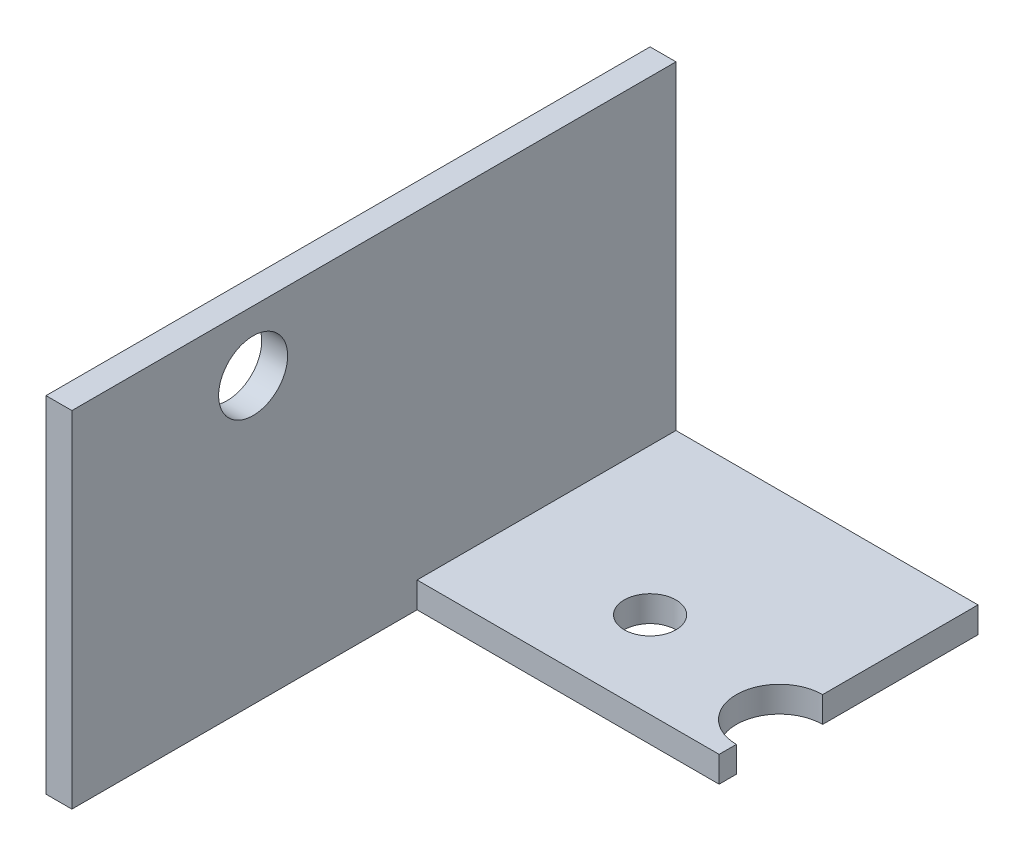
SolidWorks part; units mm, degrees
ref_plane "Plan de face" through (0, 0, 0) normal (0, 0, 1) x (1, 0, 0)
ref_plane "Plan de dessus" through (0, 0, 0) normal (0, 1, 0) x (1, 0, 0)
ref_plane "Plan de droite" through (0, 0, 0) normal (1, 0, 0) x (0, 0, -1)
sketch "Esquisse1" plane through (0, 0, 0) normal (0, 0, 1) x (1, 0, 0)
  line L0 (-13.4546, 9.7732) -> (-13.4546, -10.2268)
  line L1 (-13.4546, -10.2268) -> (5.5454, -10.2268)
  line L2 (5.5454, -10.2268) -> (5.5454, -8.7268)
  line L3 (5.5454, -8.7268) -> (-11.9546, -8.7268)
  line L4 (-11.9546, -8.7268) -> (-11.9546, 9.7732)
  line L5 (-11.9546, 9.7732) -> (-13.4546, 9.7732)
  dimension "D1" = 1.5
  dimension "D2" = 1.5
  dimension "D3" = 19
  dimension "D4" = 20
extrude "Extrusion1" add sketch "Esquisse1" along normal blind 35
sketch "Esquisse2" plane through (-11.9546, 0, 0) normal (1, 0, 0) x (0, 0, -1)
  line L0 (-35, -8.7268) -> (-35, 9.7732) construction
  line L1 (-35, 9.7732) -> (0, 9.7732) construction
  circle A0 centre (-24.5, 6.2732) radius 2
  point P2 (-35, 0.5232)
  dimension "D1" = 10.5
  dimension "D2" = 3.5
extrude "Extrusion2" cut sketch "Esquisse2" against normal blind 17
sketch "Esquisse4" plane through (0, -8.7268, 0) normal (0, 1, 0) x (-1, 0, 0)
  line L0 (11.9546, 35) -> (11.9546, 0) construction
  line L1 (-5.5454, 35) -> (11.9546, 35)
  line L2 (-5.5454, 35) -> (-5.5454, 15)
  line L3 (-5.5454, 15) -> (11.9546, 15)
  line L4 (11.9546, 35) -> (11.9546, 15)
  line L5 (-5.5454, 35) -> (-5.5454, 0) construction
  circle A0 centre (3.4546, 10) radius 1.5
  circle A1 centre (-5.5454, 11.5) radius 2.5
  dimension "D2" = 5
  dimension "D4" = 3.5
  dimension "D1" = 20
  dimension "D3" = 8.5
extrude "Extrusion3" cut sketch "Esquisse4" against normal blind 17
